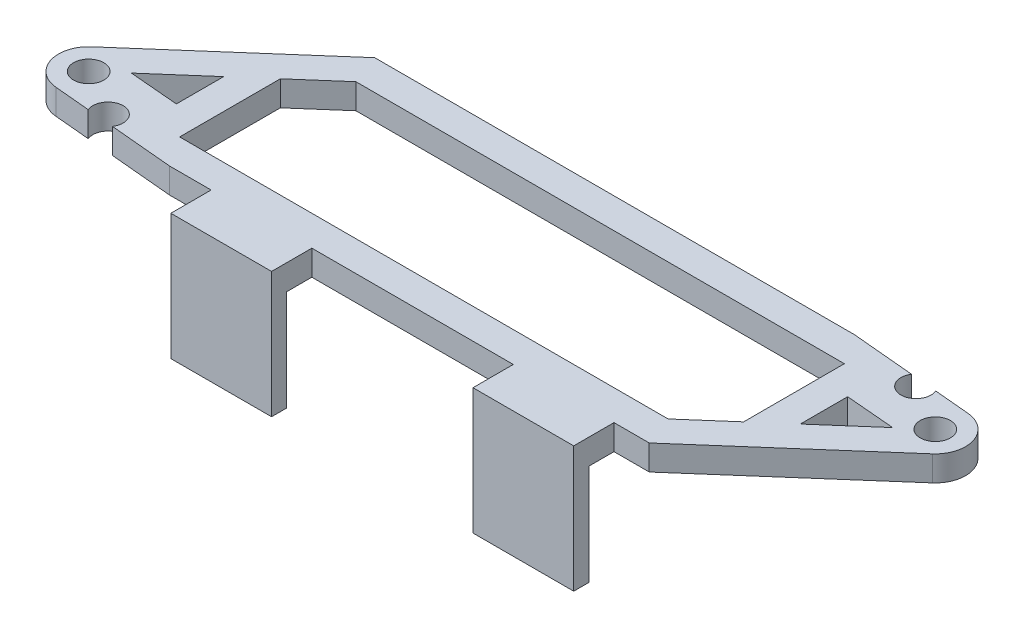
SolidWorks part; units mm, degrees
ref_plane "Front Plane" through (0, 0, 0) normal (0, 0, 1) x (1, 0, 0)
ref_plane "Top Plane" through (0, 0, 0) normal (0, 1, 0) x (1, 0, 0)
ref_plane "Right Plane" through (0, 0, 0) normal (1, 0, 0) x (0, 0, -1)
sketch "Sketch1" plane through (0, 0, 0) normal (0, 1, 0) x (1, 0, 0)
  line L0 (-44.5, 27) -> (52.5, 27)
  line L1 (52.5, 27) -> (52.5, 7)
  line L2 (44.5, 0) -> (-52.5, 0)
  line L3 (-52.5, 0) -> (-52.5, 20)
  line L4 (0, 0) -> (0, 73.3696) construction
  line L5 (-46.7544, 33) -> (48.5, 33)
  line L6 (-46.7544, 33) -> (-76.75, 6.7539)
  line L7 (46.7544, -6) -> (76.75, 20.2461)
  line L8 (46.7544, -6) -> (39.7544, -6)
  line L9 (44.5, 0) -> (52.5, 7)
  line L10 (58.5, 21.65) -> (58.5, 12.25)
  line L11 (58.5, 21.65) -> (68.2835, 20.8106)
  line L12 (58.5, 12.25) -> (68.2835, 20.8106)
  line L13 (48.5, 33) -> (60.9847, 31.8627)
  line L14 (66.2694, 31.3813) -> (73.3433, 30.7368)
  line L15 (-52.5, 20) -> (-44.5, 27)
  line L16 (-58.5, 14.75) -> (-68.2835, 6.1894)
  line L17 (-68.2835, 6.1894) -> (-58.5, 5.35)
  line L18 (-58.5, 5.35) -> (-58.5, 14.75)
  line L19 (-73.3433, -3.7368) -> (-66.2694, -4.3813)
  line L20 (-60.9847, -4.8627) -> (-48.5, -6)
  line L21 (19.7544, -6) -> (19.7544, -14)
  line L22 (19.7544, -14) -> (39.7544, -14)
  line L23 (39.7544, -14) -> (39.7544, -6)
  line L24 (-20.2456, -6) -> (-20.2456, -14)
  line L25 (-20.2456, -14) -> (-40.2456, -14)
  line L26 (-40.2456, -14) -> (-40.2456, -6)
  line L27 (-40.2456, -6) -> (-48.5, -6)
  line L28 (19.7544, -6) -> (-20.2456, -6)
  circle A0 centre (72.799, 24.7616) radius 3
  arc A1 (76.75, 20.2461) -> (73.3433, 30.7368) centre (72.799, 24.7616) ccw
  arc A2 (60.9847, 31.8627) -> (66.2694, 31.3813) centre (63.5, 30.2277) ccw
  circle A3 centre (-72.799, 2.2384) radius 3
  arc A4 (-76.75, 6.7539) -> (-73.3433, -3.7368) centre (-72.799, 2.2384) ccw
  arc A5 (-66.2694, -4.3813) -> (-60.9847, -4.8627) centre (-63.5, -3.2277) cw
  dimension "D10" = 3
  dimension "D11" = 6
  dimension "D12" = 13
  dimension "D15" = 3
  dimension "D14" = 3
  dimension "D21" = 13
  dimension "D23" = 3
  dimension "D24" = 3
  dimension "D25" = 6
  dimension "D26" = 4
  dimension "D27" = 3
  dimension "D1" = 6
  dimension "D2" = 105
  dimension "D3" = 6
  dimension "D4" = 6
  dimension "D5" = 97
  dimension "D6" = 20
  dimension "D7" = 27
  dimension "D8" = 6
  dimension "D9" = 6
  dimension "D13" = 4
  dimension "D16" = 9.4
  dimension "D17" = 20
  dimension "D18" = 97
  dimension "D19" = 6
  dimension "D20" = 6
  dimension "D22" = 9.4
  dimension "D28" = 1.4
  dimension "D29" = 15
  dimension "D30" = 15
  dimension "D31" = 1.4
  dimension "D32" = 8
  dimension "D33" = 20
  dimension "D34" = 20
  dimension "D35" = 40
  dimension "D36" = 7
extrude "Boss-Extrude1" add sketch "Sketch1" along normal blind 5
sketch "Sketch2" plane through (0, 0, 0) normal (0, -1, 0) x (1, 0, 0)
  line L1 (-40.2456, 14) -> (-20.2456, 14)
  line L2 (-40.2456, 14) -> (-40.2456, 11)
  line L3 (-40.2456, 11) -> (-20.2456, 11)
  line L4 (-20.2456, 14) -> (-20.2456, 11)
  line L5 (39.7544, 14) -> (39.7544, 6) construction
  line L6 (19.7544, 14) -> (39.7544, 14)
  line L7 (19.7544, 14) -> (19.7544, 11)
  line L8 (19.7544, 11) -> (39.7544, 11)
  line L9 (39.7544, 14) -> (39.7544, 11)
  line L10 (-20.2456, 14) -> (-20.2456, 6) construction
  dimension "D1" = 3
extrude "Boss-Extrude2" add sketch "Sketch2" along normal blind 20
